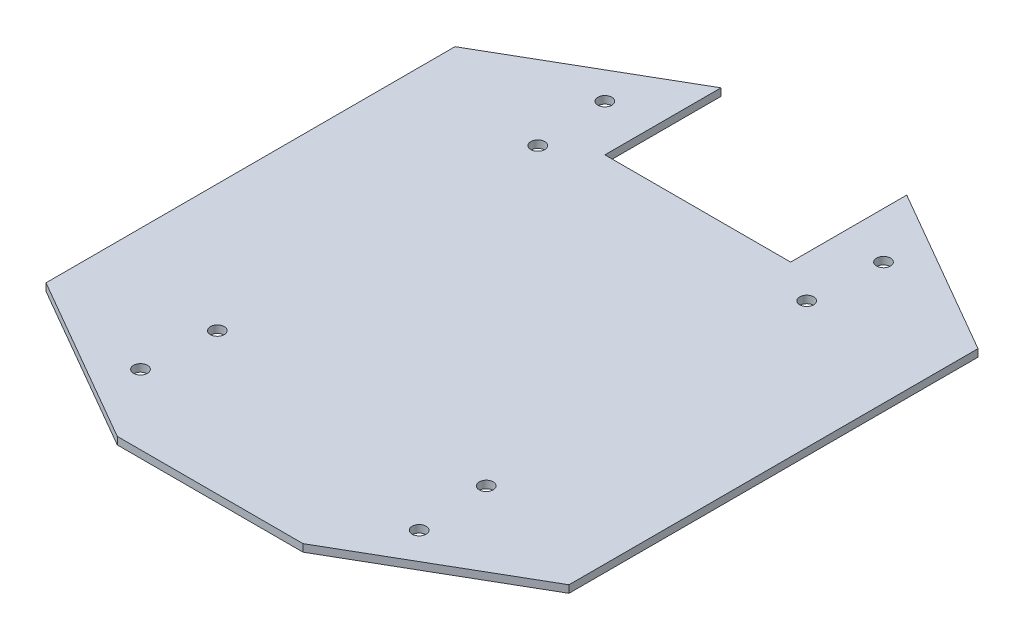
SolidWorks part; units mm, degrees
ref_plane "Front Plane" through (0, 0, 0) normal (0, 0, 1) x (1, 0, 0)
ref_plane "Top Plane" through (0, 0, 0) normal (0, 1, 0) x (1, 0, 0)
ref_plane "Right Plane" through (0, 0, 0) normal (1, 0, 0) x (0, 0, -1)
sketch "Sketch3" plane through (0, 0, 0) normal (0, 1, 0) x (1, 0, 0)
  line L0 (-20, 65) -> (20, 65)
  line L1 (65, 39.0192) -> (65, -39.0192)
  line L3 (-65, -39.0192) -> (-65, 39.0192)
  line L4 (-20, 65) -> (-65, 39.0192)
  line L5 (20, 65) -> (65, 39.0192)
  line L6 (0, 0) -> (-65, 0) construction
  line L7 (20, -65) -> (65, -39.0192)
  line L8 (-20, -65) -> (-65, -39.0192)
  line L9 (-20, -65) -> (20, -65)
  point P2 (65, 0)
  point P5 (-65, 0)
  dimension "D1" = 78.0385
  dimension "D2" = 130
  dimension "D3" = 0
  dimension "D4" = 150
  dimension "D5" = 150
  dimension "D6" = 40
  dimension "D7" = 130
  dimension "D8" = 65
extrude "Boss-Extrude1" add sketch "Sketch3" along normal blind 1.6
sketch "Sketch4" plane through (0, 1.6, 0) normal (0, 1, 0) x (1, 0, 0)
  line L0 (-61.5798, 40.9939) -> (-65, 31.597)
  line L1 (-20, 65) -> (-65, 39.0192) construction
  line L2 (-65, 39.0192) -> (-65, -39.0192) construction
  line L3 (65, 31.597) -> (61.5798, 40.9939)
  line L4 (65, -39.0192) -> (65, 39.0192) construction
  line L5 (65, 39.0192) -> (20, 65) construction
  line L6 (61.5798, 40.9939) -> (65, 39.0192)
  line L7 (65, 39.0192) -> (65, 31.597)
  line L8 (-61.5798, 40.9939) -> (-65, 39.0192)
  line L9 (-65, 39.0192) -> (-65, 31.597)
  line L10 (0, 0) -> (-65, 0) construction
  line L11 (61.5798, -40.9939) -> (65, -39.0192)
  line L12 (65, -31.597) -> (61.5798, -40.9939)
  line L13 (65, -39.0192) -> (65, -31.597)
  line L14 (-61.5798, -40.9939) -> (-65, -39.0192)
  line L15 (-61.5798, -40.9939) -> (-65, -31.597)
  line L16 (-65, -39.0192) -> (-65, -31.597)
  dimension "D1" = 160
  dimension "D2" = 10
  dimension "D3" = 160
  dimension "D4" = 10
extrude "Cut-Extrude1" cut sketch "Sketch4" against normal up to surface (1.6 mm away) up to face at (0, 0, 0)
sketch "Sketch5" plane through (0, 1.6, 0) normal (0, 1, 0) x (1, 0, 0)
  line L1 (-30, -50) -> (30, -50) construction
  line L2 (-30, -50) -> (-30, 50) construction
  line L3 (-30, 50) -> (30, 50) construction
  line L4 (30, -50) -> (30, 50) construction
  line L5 (-30, -50) -> (30, 50) construction
  line L6 (-30, 50) -> (30, -50) construction
  circle A0 centre (-30, 50) radius 1.5
  circle A1 centre (30, 50) radius 1.5
  circle A2 centre (30, -50) radius 1.5
  circle A3 centre (-30, -50) radius 1.5
  point P0 (0, 0)
  dimension "D3" = 3
  dimension "D1" = 60
  dimension "D2" = 100
extrude "Cut-Extrude2" cut sketch "Sketch5" against normal up to surface (1.6 mm away) up to face at (0, 0, 0)
sketch "Sketch6" plane through (0, 1.6, 0) normal (0, 1, 0) x (1, 0, 0)
  line L0 (0, 0) -> (0, 65) construction
  line L1 (-65, 31.597) -> (-76.5004, 0)
  line L2 (20, 65) -> (-20, 65) construction
  line L3 (-65, -31.597) -> (-76.5004, 0)
  line L4 (-65, 31.597) -> (-65, -31.597)
  line L5 (65, 31.597) -> (65, -31.597)
  line L6 (65, -31.597) -> (76.5004, 0)
  line L7 (65, 31.597) -> (76.5004, 0)
  dimension "D1" = 220
  dimension "D2" = 31.597
extrude "Boss-Extrude2" add sketch "Sketch6" against normal up to surface (1.6 mm away) up to face at (-30, 0, 48.5)
sketch "Sketch8" [suppressed] plane through (0, 1.6, 0) normal (0, 1, 0) x (1, 0, 0)
  line L0 (-69.221, 20) -> (-69.221, -20)
  line L1 (-76.5004, 0) -> (-61.5798, 40.9939) construction
  line L2 (-61.5798, -40.9939) -> (-76.5004, 0) construction
  line L3 (-69.221, -20) -> (-76.5004, 0)
  line L4 (-76.5004, 0) -> (-69.221, 20)
  line L5 (69.221, 20) -> (69.221, -20)
  line L6 (61.5798, 40.9939) -> (76.5004, 0) construction
  line L7 (76.5004, 0) -> (61.5798, -40.9939) construction
  line L8 (69.221, -20) -> (76.5004, 0)
  line L9 (76.5004, 0) -> (69.221, 20)
  dimension "D1" = 40
  dimension "D2" = 40
extrude "Cut-Extrude3" [suppressed] cut sketch "Sketch8" against normal up to surface (1.6 mm away)
sketch "Sketch9" plane through (0, 1.6, 0) normal (0, 1, 0) x (1, 0, 0)
  line L1 (-30, -38) -> (30, -38) construction
  line L2 (-30, -38) -> (-30, 38) construction
  line L3 (-30, 38) -> (30, 38) construction
  line L4 (30, -38) -> (30, 38) construction
  line L5 (-30, -38) -> (30, 38) construction
  line L6 (-30, 38) -> (30, -38) construction
  circle A2 centre (30, -38) radius 1.5
  circle A3 centre (-30, -38) radius 1.5
  point P0 (0, 0)
  dimension "D3" = 3
  dimension "D1" = 60
  dimension "D2" = 76
extrude "Cut-Extrude4" [suppressed] cut sketch "Sketch9" against normal up to surface (1.6 mm away)
sketch "Sketch10" plane through (0, 1.6, 0) normal (0, 1, 0) x (1, 0, 0)
  line L1 (-28.953, -34.5049) -> (28.953, -34.5049) construction
  line L2 (-28.953, -34.5049) -> (-28.953, 34.5049) construction
  line L3 (-28.953, 34.5049) -> (28.953, 34.5049) construction
  line L4 (28.953, -34.5049) -> (28.953, 34.5049) construction
  line L5 (-28.953, -34.5049) -> (28.953, 34.5049) construction
  line L6 (-28.953, 34.5049) -> (28.953, -34.5049) construction
  circle A0 centre (-28.953, 34.5049) radius 1.5
  circle A1 centre (28.953, 34.5049) radius 1.5
  circle A2 centre (-28.953, -34.5049) radius 1.5
  circle A3 centre (28.953, -34.5049) radius 1.5
  point P0 (0, 0)
  dimension "D3" = 3
  dimension "D1" = 57.906
  dimension "D2" = 69.0097
extrude "Cut-Extrude5" cut sketch "Sketch10" against normal up to surface (1.6 mm away) up to face at (-30, 0, 48.5)
sketch "Sketch11" plane through (0, 1.6, 0) normal (0, 1, 0) x (1, 0, 0)
  line L0 (-68.311, 22.5) -> (-68.311, -22.5)
  line L1 (-76.5004, 0) -> (-61.5798, 40.9939) construction
  line L2 (-61.5798, -40.9939) -> (-76.5004, 0) construction
  line L3 (-68.311, -22.5) -> (-76.5004, 0)
  line L4 (-76.5004, 0) -> (-68.311, 22.5)
  line L5 (68.311, 22.5) -> (68.311, -22.5)
  line L6 (61.5798, 40.9939) -> (76.5004, 0) construction
  line L7 (76.5004, 0) -> (61.5798, -40.9939) construction
  line L8 (68.311, -22.5) -> (76.5004, 0)
  line L9 (76.5004, 0) -> (68.311, 22.5)
  dimension "D1" = 45
  dimension "D2" = 45
extrude "Cut-Extrude6" cut sketch "Sketch11" against normal up to surface (1.6 mm away) up to face at (28.953, 0, -36.0049)
sketch "Sketch14" plane through (0, 1.6, 0) normal (0, 1, 0) x (1, 0, 0)
  line L0 (-20, 65) -> (-20, 40)
  line L1 (-20, 40) -> (20, 40)
  line L2 (20, 40) -> (20, 65)
  line L3 (-20, 65) -> (20, 65)
  dimension "D1" = 25
extrude "Cut-Extrude7" cut sketch "Sketch14" against normal up to surface (1.6 mm away) up to face at (0, 0, 0)
sketch "Sketch15" plane through (0, 1.6, 0) normal (0, 1, 0) x (1, 0, 0)
  line L0 (-68.311, 22.5) -> (-58.311, 22.5)
  line L1 (-58.311, 22.5) -> (-58.311, -22.5)
  line L2 (-58.311, -22.5) -> (-68.311, -22.5)
  line L3 (-68.311, 22.5) -> (-68.311, -22.5)
  line L4 (68.311, 22.5) -> (58.311, 22.5)
  line L5 (58.311, 22.5) -> (58.311, -22.5)
  line L6 (58.311, -22.5) -> (68.311, -22.5)
  line L7 (68.311, 22.5) -> (68.311, -22.5) construction
  line L8 (68.311, -22.5) -> (68.311, 22.5)
  dimension "D1" = 10
  dimension "D2" = 10
extrude "Cut-Extrude8" [suppressed] cut sketch "Sketch15" against normal up to surface (1.6 mm away)
sketch "Sketch16" plane through (0, 1.6, 0) normal (0, 1, 0) x (1, 0, 0)
  line L0 (-40.7899, 52.9969) -> (-40.7899, -52.9969)
  line L1 (-20, 65) -> (-61.5798, 40.9939) construction
  line L2 (-61.5798, -40.9939) -> (-20, -65) construction
  line L3 (-40.7899, -52.9969) -> (-61.5798, -40.9939)
  line L4 (-61.5798, -40.9939) -> (-68.311, -22.5)
  line L5 (-68.311, -22.5) -> (-68.311, 22.5)
  line L6 (-68.311, 22.5) -> (-61.5798, 40.9939)
  line L7 (-61.5798, 40.9939) -> (-40.7899, 52.9969)
  line L8 (40.7899, 52.9969) -> (40.7899, -52.9969)
  line L9 (61.5798, 40.9939) -> (20, 65) construction
  line L10 (20, -65) -> (61.5798, -40.9939) construction
  line L11 (40.7899, -52.9969) -> (61.5798, -40.9939)
  line L12 (61.5798, -40.9939) -> (68.311, -22.5)
  line L13 (68.311, -22.5) -> (68.311, 22.5)
  line L14 (68.311, 22.5) -> (61.5798, 40.9939)
  line L15 (61.5798, 40.9939) -> (40.7899, 52.9969)
extrude "Cut-Extrude9" [suppressed] cut sketch "Sketch16" against normal up to surface (1.6 mm away)
sketch "Sketch17" plane through (0, 1.6, 0) normal (0, 1, 0) x (1, 0, 0)
  line L0 (-56.311, 44.0358) -> (-56.311, -44.0358)
  line L1 (-20, 65) -> (-61.5798, 40.9939) construction
  line L2 (-61.5798, -40.9939) -> (-20, -65) construction
  line L3 (-56.311, -44.0358) -> (-61.5798, -40.9939)
  line L4 (-61.5798, -40.9939) -> (-68.311, -22.5)
  line L5 (-68.311, -22.5) -> (-68.311, 22.5)
  line L6 (-68.311, 22.5) -> (-61.5798, 40.9939)
  line L7 (-61.5798, 40.9939) -> (-56.311, 44.0358)
  line L8 (0, 0) -> (0, 40) construction
  line L9 (-20, 40) -> (20, 40) construction
  line L10 (68.311, 22.5) -> (61.5798, 40.9939)
  line L11 (68.311, -22.5) -> (68.311, 22.5)
  line L12 (61.5798, -40.9939) -> (68.311, -22.5)
  line L13 (56.311, -44.0358) -> (61.5798, -40.9939)
  line L14 (56.311, 44.0358) -> (56.311, -44.0358)
  line L15 (61.5798, 40.9939) -> (56.311, 44.0358)
  dimension "D1" = 12
extrude "Cut-Extrude10" cut sketch "Sketch17" against normal up to surface (1.6 mm away) up to face at (0, 0, -5.7143)
